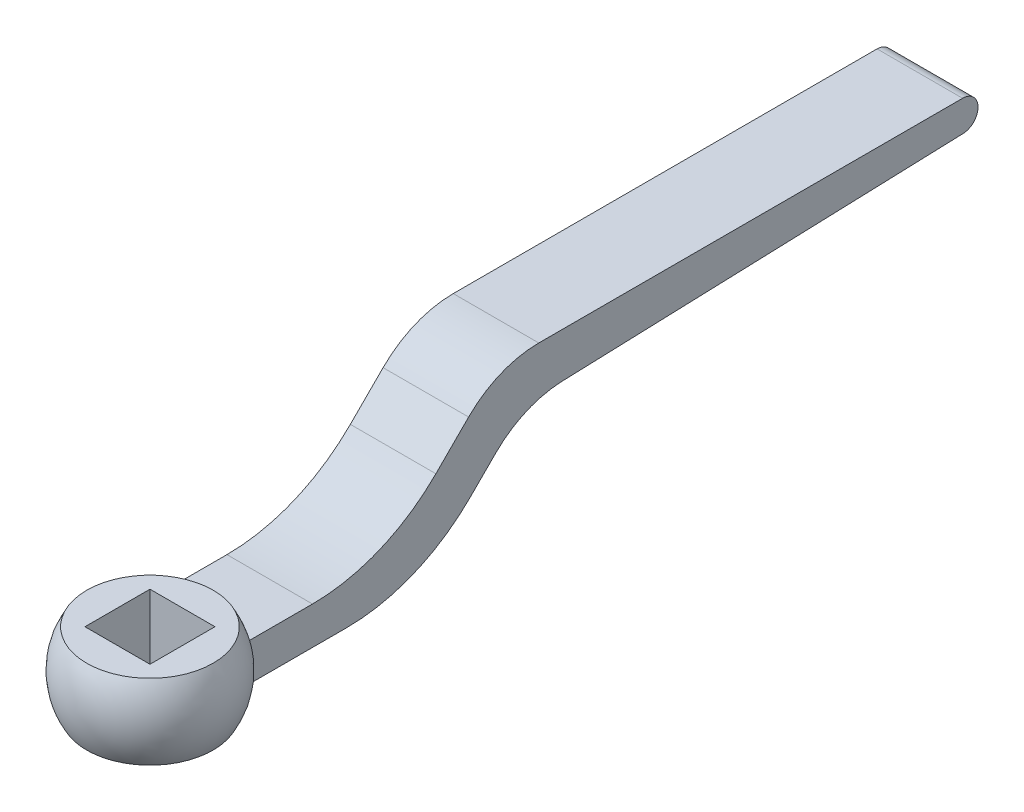
SolidWorks part; units mm, degrees
ref_plane "Front Plane" through (0, 0, 0) normal (0, 0, 1) x (1, 0, 0)
ref_plane "Top Plane" through (0, 0, 0) normal (0, 1, 0) x (1, 0, 0)
ref_plane "Right Plane" through (0, 0, 0) normal (1, 0, 0) x (0, 0, -1)
sketch "Sketch1" plane through (0, 0, 0) normal (1, 0, 0) x (0, 0, -1)
  line L0 (0, -5.5) -> (0, 5.5)
  line L1 (0, 5.5) -> (20, 5.5)
  line L2 (56.0624, 20.4376) -> (65.631, 30.0061)
  line L3 (86.1371, 38.5) -> (210, 38.5)
  line L5 (210.1571, 29.5) -> (93.0533, 25.4106)
  line L6 (73.5593, 16.9344) -> (66.0624, 9.4376)
  line L7 (30, -5.5) -> (0, -5.5)
  line L8 (0, 0) -> (-20.5836, 0) construction
  arc A0 (210.1571, 29.5) -> (210, 38.5) centre (210, 33.9986) ccw
  arc A1 (66.0624, 9.4376) -> (30, -5.5) centre (30, 45.5) cw
  arc A2 (93.0533, 25.4106) -> (73.5593, 16.9344) centre (94.0654, -3.5717) ccw
  arc A3 (86.1371, 38.5) -> (65.631, 30.0061) centre (86.1371, 9.5) ccw
  arc A4 (56.0624, 20.4376) -> (20, 5.5) centre (20, 56.5) cw
  point P6 (20.08, -5.5)
  point P7 (16.2416, 5.5)
  point P13 (23.9185, -5.5)
  point P14 (117.0751, 33.9986)
  point P22 (74.1249, 38.5)
  point P23 (22.5714, 5.5)
  point P24 (51.5709, 9.5)
  point P25 (159.8681, 33.9986)
  point P26 (0, 0)
  point P27 (31.7519, 5.5)
  dimension "D6" = 51
  dimension "D7" = 29
  dimension "D8" = 29
  dimension "D9" = 51
  dimension "D1" = 11
  dimension "D2" = 2
  dimension "D3" = 44
  dimension "D4" = 9
  dimension "D5" = 45
  dimension "D10" = 210
  dimension "D11" = 20
  dimension "D12" = 30
extrude "Boss-Extrude1" add sketch "Sketch1" along normal mid plane 25
sketch "Sketch2" plane through (0, 0, 0) normal (1, 0, 0) x (0, 0, -1)
  line L0 (-36.5, 0) -> (6.5, 0)
  arc A0 (-36.5, 0) -> (6.5, 0) centre (-15, 0) cw
  point P4 (-6.1509, 0)
  point P5 (0, 0)
  dimension "D1" = 21.5
  dimension "D2" = 15
revolve "Revolve2" add sketch "Sketch2" angle 360 about L0
sketch "Sketch3" plane through (0, 0, 0) normal (1, 0, 0) x (0, 0, -1)
  line L0 (-33.473, 11) -> (3.473, 11)
  line L1 (0, 0) -> (-53.3091, 0) construction
  line L2 (-33.473, -11) -> (3.473, -11)
  arc A0 (5.7846, 5.5) -> (5.7846, -5.5) centre (-15, 0) ccw construction
  arc A1 (3.473, 11) -> (-33.473, 11) centre (-15, 0) ccw
  arc A2 (-33.473, -11) -> (3.473, -11) centre (-15, 0) ccw
  dimension "D1" = 11
extrude "Cut-Extrude1" cut sketch "Sketch3" against normal through all both and the other way through all
sketch "Sketch4" plane through (0, 11, 0) normal (0, 1, 0) x (1, 0, 0)
  line L0 (-18.473, -15) -> (0, -15) construction
  line L1 (-9.5, -5.5) -> (9.5, -5.5)
  line L2 (-9.5, -5.5) -> (-9.5, -24.5)
  line L3 (-9.5, -24.5) -> (9.5, -24.5)
  line L4 (9.5, -5.5) -> (9.5, -24.5)
  line L5 (-9.5, -5.5) -> (9.5, -24.5) construction
  line L6 (-9.5, -24.5) -> (9.5, -5.5) construction
  circle A2 centre (0, -15) radius 18.473 construction
  point P0 (0, -15)
  point P10 (0, -12.6969)
  dimension "D1" = 19
  dimension "D2" = 19
extrude "Cut-Extrude2" cut sketch "Sketch4" against normal through all both and the other way through all
sketch "Sketch6" plane through (0, -5.5, 0) normal (0, -1, 0) x (1, 0, 0)
  line L0 (0, 15) -> (-18.473, 15) construction
  circle A0 centre (-4, -8) radius 1.5
  circle A1 centre (0, 15) radius 18.473 construction
  point P6 (0, 18.4975)
  dimension "D1" = 3
  dimension "D2" = 23
  dimension "D3" = 4
extrude "Boss-Extrude2" add sketch "Sketch6" along normal mid plane 15
